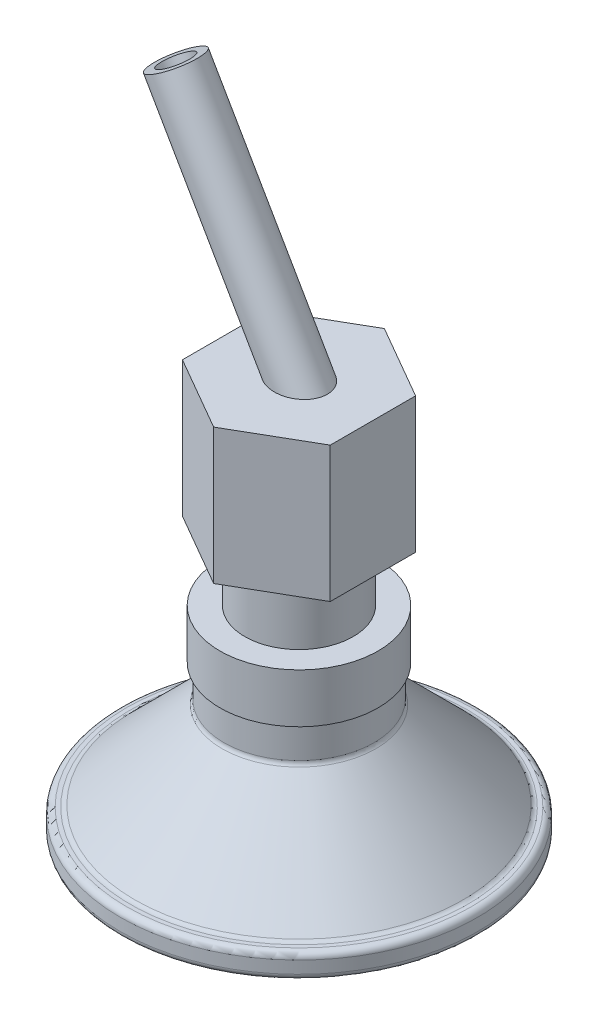
SolidWorks part; units mm, degrees
ref_plane "Plan de face" through (0, 0, 0) normal (0, 0, 1) x (1, 0, 0)
ref_plane "Plan de dessus" through (0, 0, 0) normal (0, 1, 0) x (1, 0, 0)
ref_plane "Plan de droite" through (0, 0, 0) normal (1, 0, 0) x (0, 0, -1)
sketch "Esquisse1" plane through (0, 0, 0) normal (0, 0, 1) x (1, 0, 0)
  line L0 (4.4, 10.1526) -> (4.4, 5.1526)
  line L1 (4.4, 5.1526) -> (6.4207, 5.1526)
  line L2 (6.4207, 5.1526) -> (6.4207, 1.1526)
  line L4 (6.4207, 1.1526) -> (6.4207, 5.2311) construction
  line L5 (6.4207, 5.2311) -> (8.9956, 2.6563) construction
  line L6 (8.9956, 2.6563) -> (9.5496, 2.6563) construction
  line L7 (9.5496, 2.6563) -> (9.5496, 1.8985) construction
  line L8 (9.5496, 1.8985) -> (0, 1.8985) construction
  line L9 (0, 1.8985) -> (0, 10.1526) construction
  line L10 (0, 10.1526) -> (4.4, 10.1526) construction
  line L11 (4.4, 10.1526) -> (2, 10.1526)
  line L12 (2, 10.1526) -> (2, 1.1526)
  line L13 (6.4207, 1.1526) -> (2, 1.1526)
  dimension "D1" = 4.4
  dimension "D2" = 5
  dimension "D3" = 4
  dimension "D4" = 2
revolve "Révolution1" add sketch "Esquisse1" angle 360 about L9
sketch "Esquisse2" plane through (0, 0, 0) normal (0, 0, 1) x (1, 0, 0)
  line L0 (6.1, 1.1526) -> (6.1, -1.6596)
  line L1 (-6.4207, 1.1526) -> (6.4207, 1.1526) construction
  line L2 (6.1, -1.6596) -> (13.4763, -9.0358)
  line L3 (13.4763, -9.0358) -> (14.5007, -9.0358)
  line L4 (14.5007, -9.0358) -> (14.5007, -11.0358)
  line L5 (14.5007, -11.0358) -> (6.5914, -11.0358)
  line L6 (6.5914, -11.0358) -> (6.5914, -9.0358)
  line L7 (6.5914, -9.0358) -> (12.0621, -9.0358)
  line L8 (12.0621, -9.0358) -> (5.1, -2.0738)
  line L9 (5.1, -2.0738) -> (5.1, 1.1526)
  line L10 (5.1, 1.1526) -> (6.1, 1.1526)
  line L11 (0, 10.1526) -> (0, 1.1526) construction
  line L12 (2, 10.1526) -> (-2, 10.1526) construction
  point P16 (10.546, -11.0358)
  dimension "D1" = 6.1
  dimension "D2" = 1
  dimension "D3" = 1
  dimension "D4" = 2
revolve "Révolution2" add sketch "Esquisse2" angle 360 about L11
fillet "Congé1" radius 0.5 4 edges at (0, -1.6596, 6.1) (0, -11.0358, 14.5007) (0, -9.0358, 14.5007) (0, -9.0358, 13.4763)
sketch "Esquisse3" plane through (0, 10.1526, 0) normal (0, 1, 0) x (1, 0, 0)
  line L0 (0, 0) -> (0, 12.0621) construction
  line L1 (6, 3.4641) -> (0, 6.9282)
  line L2 (0, 6.9282) -> (-6, 3.4641)
  line L3 (-6, 3.4641) -> (-6, -3.4641)
  line L4 (-6, -3.4641) -> (0, -6.9282)
  line L5 (0, -6.9282) -> (6, -3.4641)
  line L6 (6, -3.4641) -> (6, 3.4641)
  circle A0 centre (0, 0) radius 6 construction
  circle A1 centre (0, 0) radius 12.0621 construction
  circle A2 centre (0, 0) radius 2
  circle A3 centre (0, 0) radius 2 construction
  dimension "D1" = 12
extrude "Boss.-Extru.1" add sketch "Esquisse3" along normal blind 11
sketch "Esquisse4" plane through (0, 0, 0) normal (0, 0, 1) x (1, 0, 0)
  line L0 (0, 21.1526) -> (-9.9817, 38.4413) construction
  line L1 (-6, 21.1526) -> (0, 21.1526) construction
  dimension "D1" = 60
ref_plane "Plan1" through (0, 21.1526, 0) normal (-0.5, 0.866, 0) x (0.866, 0.5, 0)
sketch "Esquisse5" plane through (0, 21.1526, 0) normal (-0.5, 0.866, 0) x (0.866, 0.5, 0)
  circle A0 centre (0, 0) radius 1.3
  circle A1 centre (0, 0) radius 2
  dimension "D1" = 0.7
  dimension "D2" = 4
extrude "Boss.-Extru.3" add sketch "Esquisse5" along normal blind 20 and the other way blind 3 separate body
